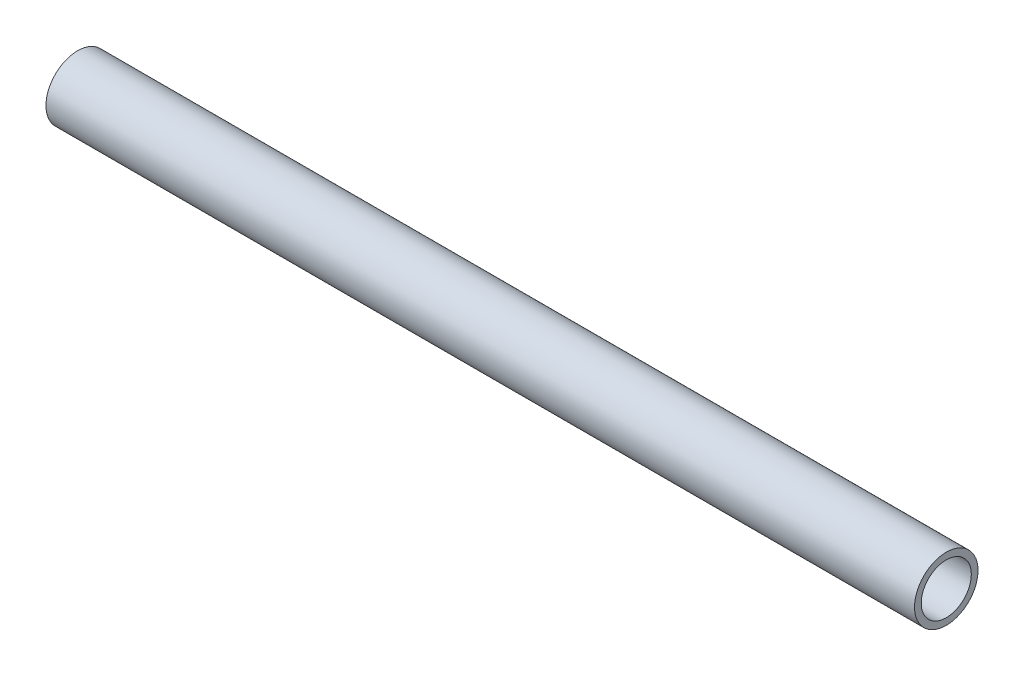
SolidWorks part; units mm, degrees
ref_plane "Alzado" through (0, 0, 0) normal (0, 0, 1) x (1, 0, 0)
ref_plane "Planta" through (0, 0, 0) normal (0, 1, 0) x (1, 0, 0)
ref_plane "Vista lateral" through (0, 0, 0) normal (1, 0, 0) x (0, 0, -1)
sketch "Croquis1" plane through (0, 0, 0) normal (1, 0, 0) x (0, 0, -1)
  circle A0 centre (0, 0) radius 19
  circle A1 centre (0, 0) radius 15
extrude "Saliente-Extruir1" add sketch "Croquis1" along normal blind 520
